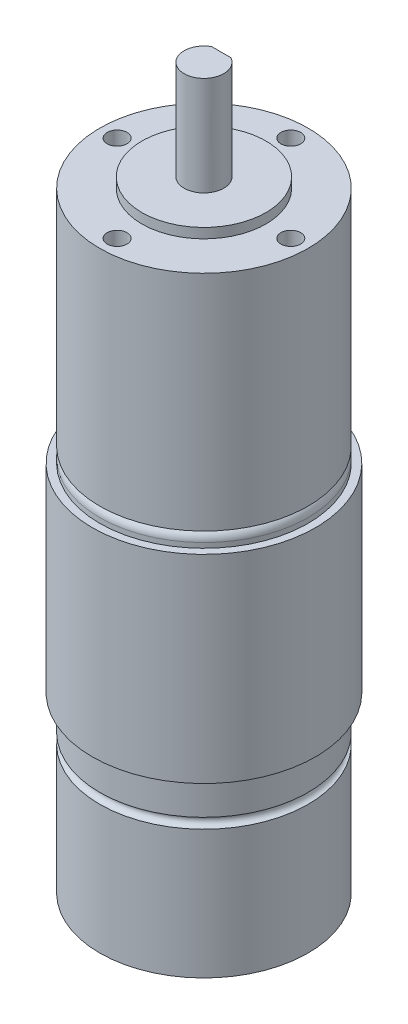
SolidWorks part; units mm, degrees
ref_plane "Front Plane" through (0, 0, 0) normal (0, 0, 1) x (1, 0, 0)
ref_plane "Top Plane" through (0, 0, 0) normal (0, 1, 0) x (1, 0, 0)
ref_plane "Right Plane" through (0, 0, 0) normal (1, 0, 0) x (0, 0, -1)
sketch "Sketch1" plane through (0, 0, 0) normal (0, 0, 1) x (1, 0, 0)
  line L0 (0, 145) -> (0, 0)
  line L1 (0, 145) -> (4, 145)
  line L2 (4, 145) -> (4, 125)
  line L3 (4, 125) -> (12.5, 125)
  line L4 (12.5, 125) -> (12.5, 123)
  line L5 (12.5, 123) -> (21, 123)
  line L6 (21, 123) -> (21, 78)
  line L7 (21, 78) -> (19, 78)
  line L8 (19, 78) -> (19, 76) construction
  line L9 (19, 76) -> (21, 76) construction
  line L10 (21, 76) -> (21, 75)
  line L11 (21, 75) -> (22.5, 75)
  line L12 (22.5, 75) -> (22.5, 35)
  line L13 (22.5, 35) -> (21, 35)
  line L14 (21, 35) -> (21, 28.0391)
  line L15 (21, 28.0391) -> (21, 25.9609) construction
  line L16 (21, 25.9609) -> (21, 0)
  line L17 (21, 0) -> (0, 0)
  line L18 (0, 180.021) -> (0, -84.8299) construction
  arc A0 (21, 76) -> (19, 78) centre (19, 76) ccw
  arc A1 (21, 28.0391) -> (21, 25.9609) centre (21, 27) ccw
  dimension "D8" = 1
  dimension "D1" = 145
  dimension "D2" = 8.5
  dimension "D3" = 4
  dimension "D4" = 20
  dimension "D5" = 21
  dimension "D6" = 2
  dimension "D7" = 45
  dimension "D9" = 2
  dimension "D10" = 2
  dimension "D11" = 40
  dimension "D12" = 22.5
  dimension "D13" = 21
  dimension "D14" = 0
  dimension "D15" = 27
  dimension "D16" = 0
revolve "Revolve1" add sketch "Sketch1" angle 360 about L18
sketch "Sketch2" plane through (0, 145, 0) normal (0, 1, 0) x (1, 0, 0)
  line L0 (-1.9365, 3.5) -> (1.9365, 3.5)
  arc A0 (1.9365, 3.5) -> (-1.9365, 3.5) centre (0, 0) ccw
  dimension "D1" = 3.5
extrude "Cut-Extrude1" cut sketch "Sketch2" against normal blind 12
sketch "Sketch3" plane through (0, 123, 0) normal (0, 1, 0) x (1, 0, 0)
  circle A0 centre (0, 0) radius 17.5 construction
  circle A1 centre (0, 17.5) radius 2
  circle A2 centre (17.5, 0) radius 2
  circle A3 centre (0, -17.5) radius 2
  circle A4 centre (-17.5, 0) radius 2
  point P14 (0, 0)
  dimension "D1" = 35
  dimension "D2" = 4
  dimension "D3" = 4
extrude "Cut-Extrude2" cut sketch "Sketch3" against normal blind 4
